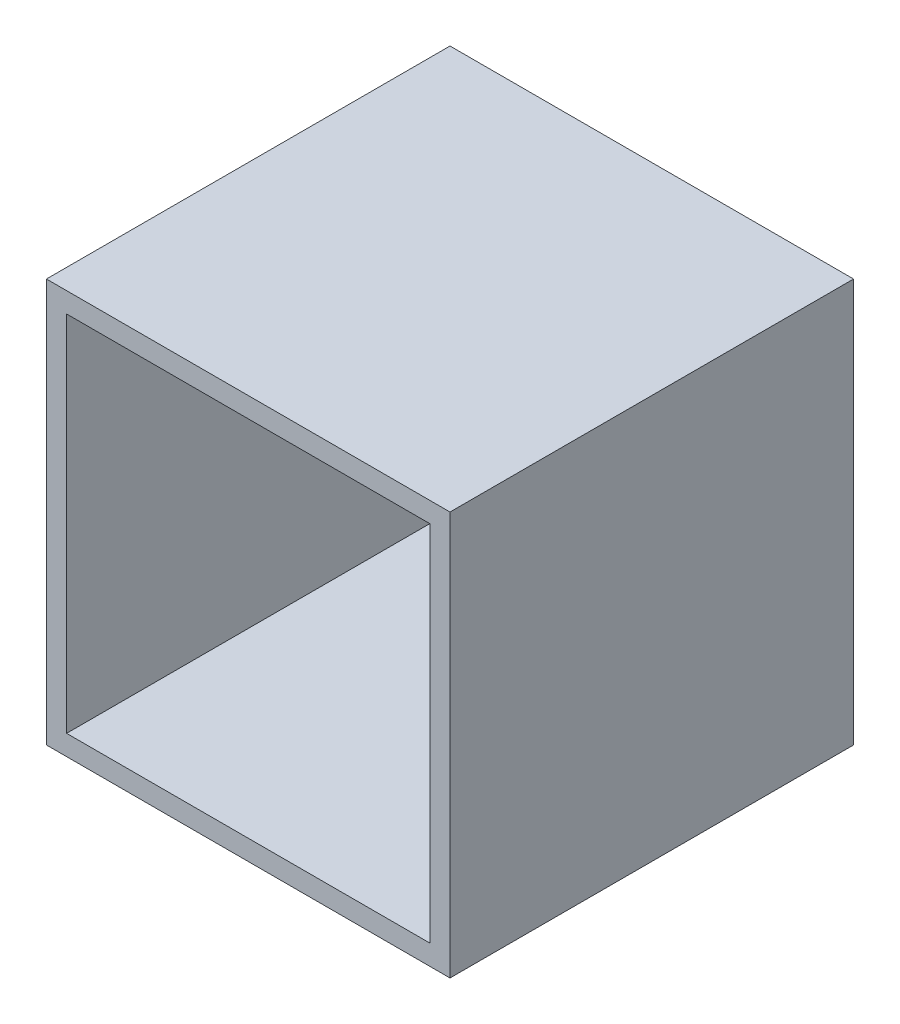
SolidWorks part; units mm, degrees
ref_plane "Front" through (0, 0, 0) normal (0, 0, 1) x (1, 0, 0)
ref_plane "Top" through (0, 0, 0) normal (0, 1, 0) x (1, 0, 0)
ref_plane "Right" through (0, 0, 0) normal (1, 0, 0) x (0, 0, -1)
other "Configuration Table"
sketch "Sketch1" plane through (0, 0, 0) normal (0, 0, 1) x (1, 0, 0)
  line L1 (0, 0) -> (100, 0)
  line L2 (0, 0) -> (0, 100)
  line L3 (0, 100) -> (100, 100)
  line L4 (100, 0) -> (100, 100)
  dimension "D1" = 100
  dimension "D2" = 100
extrude "Boss-Extrude1" add sketch "Sketch1" along normal blind 100
shell "Shell1" thickness 5
